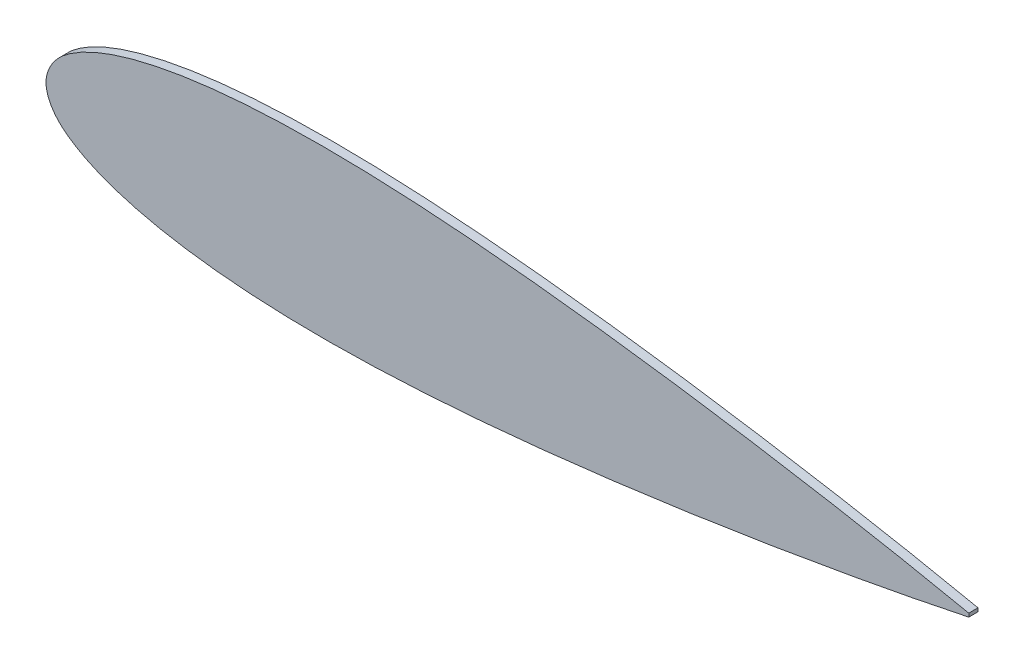
SolidWorks part; units mm, degrees
ref_plane "Front Plane" through (0, 0, 0) normal (0, 0, 1) x (1, 0, 0)
ref_plane "Top Plane" through (0, 0, 0) normal (0, 1, 0) x (1, 0, 0)
ref_plane "Right Plane" through (0, 0, 0) normal (1, 0, 0) x (0, 0, -1)
curve "Curve1"
  spline degree 3 poles (1, 0.0019, 0) (0.9833, 0.0053, 0) (0.9501, 0.0122, 0) (0.8834, 0.025, 0) (0.8002, 0.0397, 0) (0.7001, 0.0553, 0) (0.6002, 0.0688, 0) (0.5002, 0.0799, 0) (0.4001, 0.0878, 0) (0.3167, 0.0906, 0) (0.25, 0.0895, 0) (0.1999, 0.0865, 0) (0.1497, 0.0808, 0) (0.1079, 0.0728, 0) (0.0746, 0.0633, 0) (0.0492, 0.0537, 0) (0.0279, 0.0421, 0) (0.0083, 0.0261, 0) (-0.0054, 0, 0) (0.0083, -0.0261, 0) (0.0279, -0.0421, 0) (0.0492, -0.0537, 0) (0.0746, -0.0633, 0) (0.1079, -0.0728, 0) (0.1497, -0.0808, 0) (0.1999, -0.0865, 0) (0.25, -0.0895, 0) (0.3167, -0.0906, 0) (0.4001, -0.0878, 0) (0.5002, -0.0799, 0) (0.6002, -0.0688, 0) (0.7001, -0.0553, 0) (0.8002, -0.0397, 0) (0.8834, -0.025, 0) (0.9501, -0.0122, 0) (0.9833, -0.0053, 0) (1, -0.0019, 0) knots 0 0 0 0 0.024604 0.049152 0.098109 0.146905 0.195555 0.244056 0.29241 0.340644 0.364754 0.388906 0.413178 0.437756 0.450305 0.46323 0.477068 0.485036 0.5 0.514964 0.522932 0.53677 0.549695 0.562244 0.586822 0.611094 0.635246 0.659356 0.70759 0.755944 0.804445 0.853095 0.901891 0.950848 0.975396 1 1 1 1
sketch "Sketch1" plane through (0, 0, 0) normal (0, 0, 1) x (1, 0, 0)
  line L0 (0, 0) -> (1, 0) construction
  line L1 (1, 0.0019) -> (1, -0.0019)
  spline S1 degree 3 poles (1, 0.0019) (0.9833, 0.0053) (0.9501, 0.0122) (0.8834, 0.025) (0.8002, 0.0397) (0.7001, 0.0553) (0.6002, 0.0688) (0.5002, 0.0799) (0.4001, 0.0878) (0.3167, 0.0906) (0.25, 0.0895) (0.1999, 0.0865) (0.1497, 0.0808) (0.1079, 0.0728) (0.0746, 0.0633) (0.0492, 0.0537) (0.0279, 0.0421) (0.0083, 0.0261) (-0.0054, 0) (0.0083, -0.0261) (0.0279, -0.0421) (0.0492, -0.0537) (0.0746, -0.0633) (0.1079, -0.0728) (0.1497, -0.0808) (0.1999, -0.0865) (0.25, -0.0895) (0.3167, -0.0906) (0.4001, -0.0878) (0.5002, -0.0799) (0.6002, -0.0688) (0.7001, -0.0553) (0.8002, -0.0397) (0.8834, -0.025) (0.9501, -0.0122) (0.9833, -0.0053) (1, -0.0019) knots 0 0 0 0 0.024604 0.049152 0.098109 0.146905 0.195555 0.244056 0.29241 0.340644 0.364754 0.388906 0.413178 0.437756 0.450305 0.46323 0.477068 0.485036 0.5 0.514964 0.522932 0.53677 0.549695 0.562244 0.586822 0.611094 0.635246 0.659356 0.70759 0.755944 0.804445 0.853095 0.901891 0.950848 0.975396 1 1 1 1
extrude "Boss-Extrude1" add sketch "Sketch1" along normal blind 0.01
